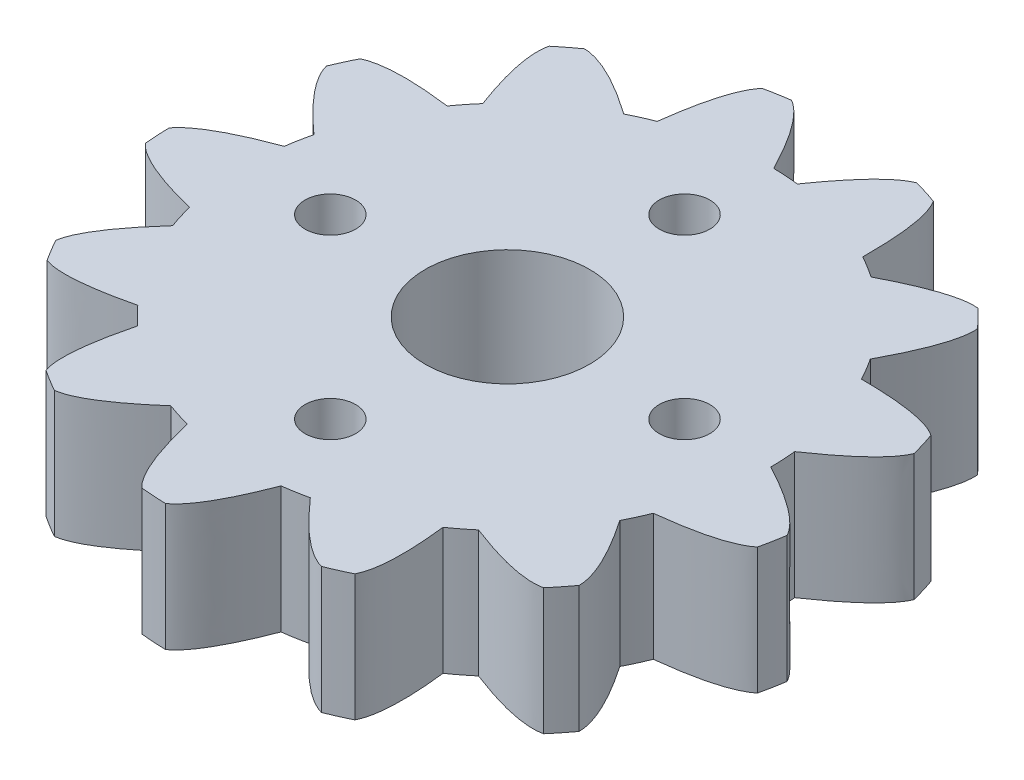
SolidWorks part; units mm, degrees
material "ABS"
ref_plane "Front Plane" through (0, 0, 0) normal (0, 0, 1) x (1, 0, 0)
ref_plane "Top Plane" through (0, 0, 0) normal (0, 1, 0) x (1, 0, 0)
ref_plane "Right Plane" through (0, 0, 0) normal (1, 0, 0) x (0, 0, -1)
sketch "Sketch1" plane through (0, 0, 0) normal (0, 1, 0) x (1, 0, 0)
  line L0 (5.8226, 8.5509) -> (8.6172, 5.7239) construction
  line L2 (7.2199, 7.1374) -> (9.3534, 9.2465) construction
  line L3 (9.3534, 9.2465) -> (9.4903, 9.3819)
  circle A0 centre (0, 0) radius 10.3451
  circle A1 centre (0, 0) radius 13.1523
  spline S0 degree 2 poles (8.6172, 5.7239) (11.7607, 11.6263) (5.8226, 8.5509) knots 0 0 0 1 1 1
  point P3 (5.8226, 8.5509)
  point P4 (8.6172, 5.7239)
  point P6 (8.9951, 9.5954)
  point P12 (4.9701, 9.0729)
  point P14 (9.4903, 9.3819)
  point P15 (9.6982, 8.8843)
  point P16 (4.3729, 9.3754)
  dimension "D1" = 20.6901
  dimension "D4" = 3
  dimension "D5" = 1
  dimension "D2" = 4
  dimension "D3" = 1
extrude "Boss-Extrude4" add sketch "Sketch1" along normal blind 5 contours A0 | A0 S0 A1
pattern_circular "CirPattern6" count 13 every 27.692 about axis through (0, 5, 0) along (0, 1, 0) of "Boss-Extrude4"
sketch "Sketch2" plane through (0, 5, 0) normal (0, 1, 0) x (1, 0, 0)
  circle A0 centre (0, 0) radius 3.25
  dimension "D1" = 6.5
extrude "Cut-Extrude1" cut sketch "Sketch2" against normal blind 10
sketch "Sketch5" plane through (0, 5, 0) normal (0, 1, 0) x (1, 0, 0)
  circle A0 centre (0, 0) radius 3.25 construction
  circle A1 centre (7, 0) radius 1
  dimension "D1" = 2
  dimension "D2" = 7
extrude "Cut-Extrude2" cut sketch "Sketch5" against normal blind 10
pattern_circular "CirPattern7" count 4 over 360 about axis through (0, 0, 0) along (0, 1, 0) of "Cut-Extrude2"
equation "\"number-of-teeth\"= 13"
equation "\"gear-size\"= 4mm"
equation "\"circumference\"= \"number-of-teeth\" * ( ( 1 + \"space-between-teeth\" ) * \"gear-size\" )"
equation "\"space-between-teeth\"= .25"
equation "\"D1@Sketch1\" = \"circumference\" / pi"
equation "\"D2@Sketch1\"=\"gear-size\""
equation "\"gear-length\"= 3mm"
equation "\"D4@Sketch1\"=\"gear-length\""
equation "\"D5@Sketch1\"=\"gear-size\" * \"space-between-teeth\""
equation "\"D3@Sketch1\"=\"gear-size\" * \"space-between-teeth\""
equation "\"D1@CirPattern6\"=\"number-of-teeth\""
equation "\"D2@CirPattern6\"=360 / \"number-of-teeth\""
